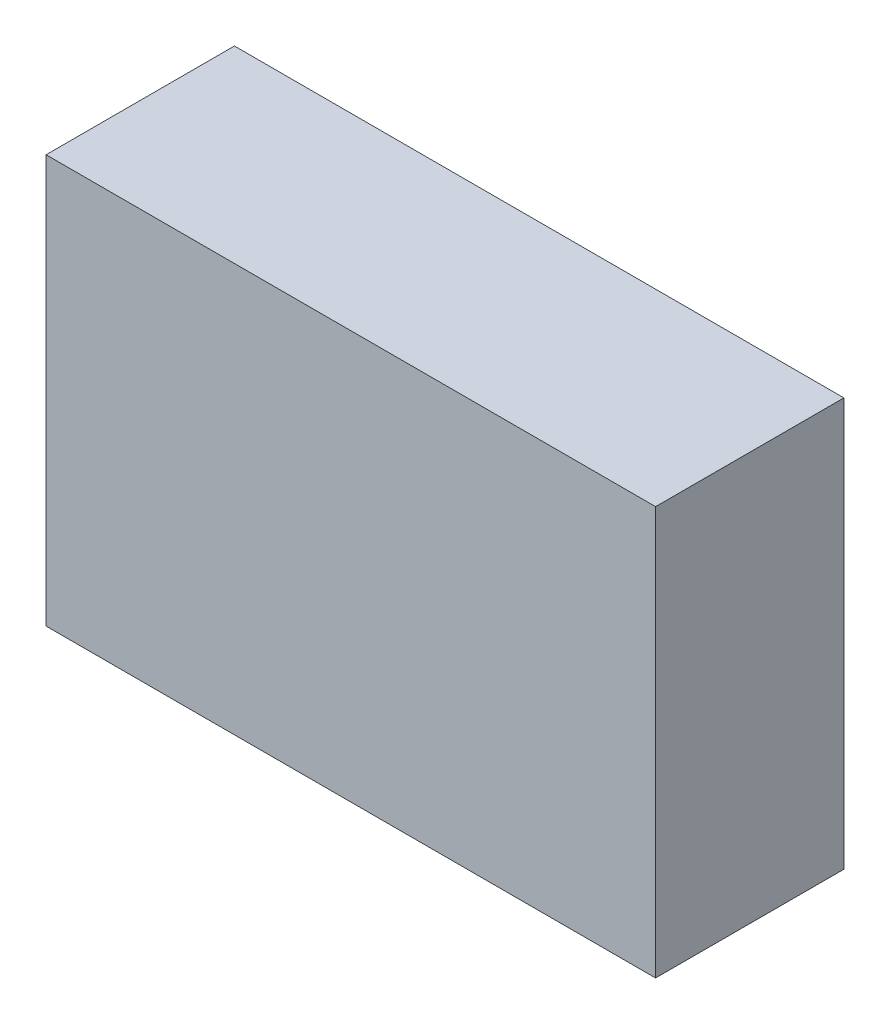
SolidWorks part; units mm, degrees
ref_plane "Front Plane" through (0, 0, 0) normal (0, 0, 1) x (1, 0, 0)
ref_plane "Top Plane" through (0, 0, 0) normal (0, 1, 0) x (1, 0, 0)
ref_plane "Right Plane" through (0, 0, 0) normal (1, 0, 0) x (0, 0, -1)
sketch "Sketch1" plane through (0, 0, 0) normal (0, 0, 1) x (1, 0, 0)
  line L1 (0, 0) -> (75.4, 0)
  line L2 (0, 0) -> (0, 50.5)
  line L3 (0, 50.5) -> (75.4, 50.5)
  line L4 (75.4, 0) -> (75.4, 50.5)
  dimension "D1" = 50.5
  dimension "D2" = 75.4
extrude "Boss-Extrude1" add sketch "Sketch1" along normal blind 23.3
